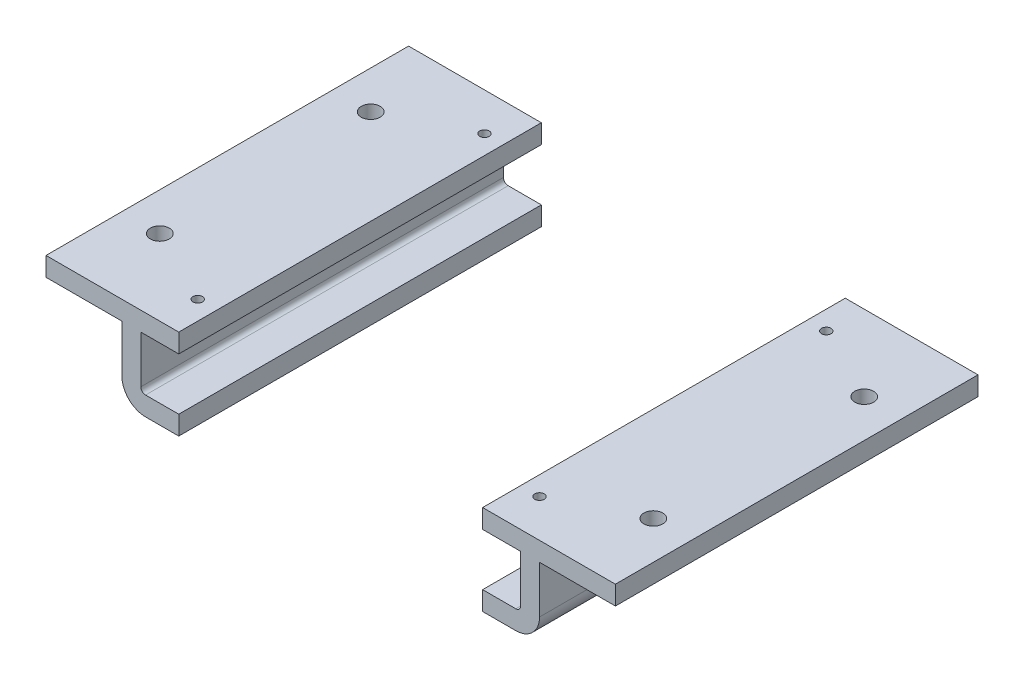
SolidWorks part; units mm, degrees
material "ABS"
ref_plane "Front" through (0, 0, 0) normal (0, 0, 1) x (1, 0, 0)
ref_plane "Top" through (0, 0, 0) normal (0, 1, 0) x (1, 0, 0)
ref_plane "Right" through (0, 0, 0) normal (1, 0, 0) x (0, 0, -1)
sketch "Sketch1" plane through (0, 0, 0) normal (0, 0, 1) x (1, 0, 0)
  line L0 (69.9262, 17.4625) -> (69.9262, 1.5875)
  line L1 (50.8762, 23.8125) -> (95.3262, 23.8125)
  line L2 (61.9887, -6.35) -> (50.8762, -6.35)
  line L3 (50.8762, -6.35) -> (50.8762, 0)
  line L4 (50.8762, 0) -> (61.9887, 0)
  line L5 (63.5762, 1.5875) -> (63.5762, 17.4625)
  line L6 (63.5762, 17.4625) -> (50.8762, 17.4625)
  line L7 (50.8762, 17.4625) -> (50.8762, 23.8125)
  line L8 (0, 1.8543) -> (0, -12.2758) construction
  line L18 (95.3262, 23.8125) -> (95.3262, 17.4625)
  line L19 (95.3262, 17.4625) -> (69.9262, 17.4625)
  arc A1 (61.9887, -6.35) -> (69.9262, 1.5875) centre (61.9887, 1.5875) ccw
  arc A2 (61.9887, 0) -> (63.5762, 1.5875) centre (61.9887, 1.5875) ccw
  point P0 (0, 0)
  point P18 (0, 17.4625)
  line B0 (-61.9887, 0) -> (61.9887, 0)
  line B1 (-63.5762, 17.4625) -> (-63.5762, 1.5875)
  line B2 (63.5762, 1.5875) -> (63.5762, 17.4625)
  line B3 (63.5762, 17.4625) -> (-63.5762, 17.4625)
  arc B4 (61.9887, 0) -> (63.5762, 1.5875) centre (61.9887, 1.5875) ccw
  arc B5 (-63.5762, 1.5875) -> (-61.9887, 0) centre (-61.9887, 1.5875) ccw
  dimension "D1" = 12.7
  dimension "D2" = 12.7
  dimension "D3" = 6.35
  dimension "D4" = 25.4
sketch_block_instance "Block-Sensor Back View-1"
sketch_block "Block-Sensor Back View"
extrude "Boss-Extrude2" add sketch "Sketch1" against normal blind 121.412 contours A2 L4 L3 L2 A1 L0 L19 L18 L1 L7 L6 L5
sketch "Sketch2" plane through (0, 23.8125, 0) normal (0, 1, 0) x (1, 0, 0)
  line L0 (57.2262, 108.712) -> (57.2262, 12.7) construction
  line L1 (82.6262, 121.412) -> (82.6262, 0) construction
  line L4 (50.8762, 0) -> (95.3262, 0)
  line L5 (95.3262, 0) -> (95.3262, 121.412)
  line L6 (95.3262, 121.412) -> (50.8762, 121.412)
  line L7 (50.8762, 121.412) -> (50.8762, 0)
  line L8 (50.8762, 0) -> (95.3262, 0) construction
  line L9 (95.3262, 0) -> (95.3262, 121.412) construction
  line L10 (95.3262, 121.412) -> (50.8762, 121.412) construction
  line L11 (50.8762, 121.412) -> (50.8762, 0) construction
  circle A0 centre (57.2262, 108.712) radius 1.5875
  circle A1 centre (57.2262, 12.7) radius 1.5875
  circle A2 centre (82.6262, 96.012) radius 3.175
  circle A3 centre (82.6262, 25.4) radius 3.175
  point P10 (57.2262, 60.706)
  point P15 (82.6262, 60.706)
  dimension "D2" = 3.175
  dimension "D8" = 6.35
  dimension "D3" = 12.7
  dimension "D4" = 6.35
  dimension "D5" = 12.7
  dimension "D6" = 25.4
  dimension "D7" = 25.4
  dimension "D1" = 0
extrude "Cut-Extrude1" cut sketch "Sketch2" against normal up to next
ref_plane "MidPlane" through (0, 0, 0) normal (-1, 0, 0) x (0, 0, 1)
mirror "Mirror5" about plane through (0, 0, 0) normal (-1, 0, 0) of bodies 104
